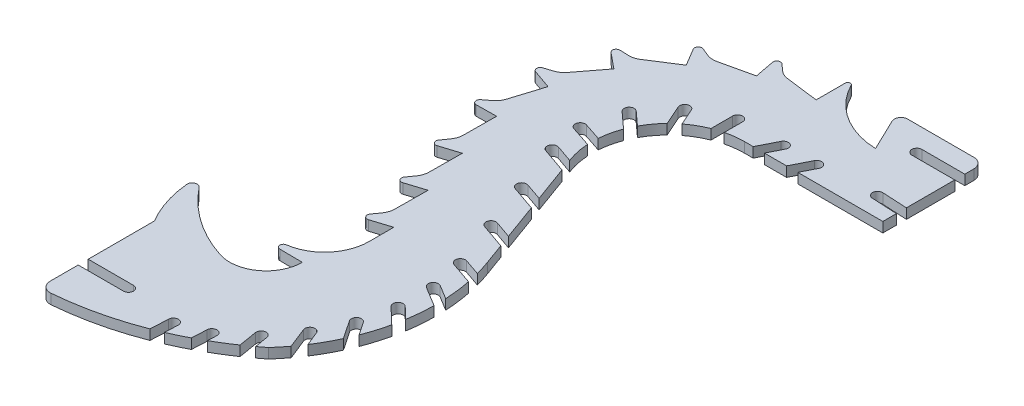
SolidWorks part; units mm, degrees
ref_plane "Front Plane" through (0, 0, 0) normal (0, 0, 1) x (1, 0, 0)
ref_plane "Top Plane" through (0, 0, 0) normal (0, 1, 0) x (1, 0, 0)
ref_plane "Right Plane" through (0, 0, 0) normal (1, 0, 0) x (0, 0, -1)
sketch "Sketch2" plane through (0, 0, 0) normal (0, 1, 0) x (1, 0, 0)
  line L0 (30.5917, -19.7066) -> (10.772, -19.7066)
  line L1 (33.5917, -22.7066) -> (33.5917, -25.4325)
  line L2 (33.5917, -25.4325) -> (20.7417, -25.4325)
  line L3 (20.7417, -28.4325) -> (33.5917, -28.4325)
  line L4 (33.5917, -28.4325) -> (33.5917, -42.9025)
  line L5 (33.5917, -42.9025) -> (26.1381, -42.5119)
  line L6 (25.9811, -45.5078) -> (33.5917, -45.9066)
  line L7 (33.5917, -45.9066) -> (33.5917, -49.9666)
  line L8 (33.5917, -49.9666) -> (8.1353, -49.9666)
  line L9 (-13.2283, -50.6294) -> (-13.2283, -45.1294)
  line L10 (-38.0968, -90.3449) -> (-15.0449, -119.6181) construction
  line L11 (-16.2283, -45.1294) -> (-16.2283, -51.5914)
  line L12 (-21.75, -54.7438) -> (-23.977, -49.7148)
  line L13 (-26.7201, -50.9295) -> (-24.1036, -56.8382)
  line L14 (-27.876, -61.9563) -> (-31.9485, -58.2597)
  line L15 (-33.9648, -60.4811) -> (-29.18, -64.8243)
  line L16 (-30.557, -71.0316) -> (-35.7774, -69.3005)
  line L17 (-36.7216, -72.1481) -> (-30.588, -74.1819)
  line L18 (-1.8534, -49.9666) -> (0.2604, -45.786)
  line L19 (-2.4169, -44.4324) -> (-5.215, -49.9666)
  line L20 (8.1353, -49.9666) -> (10.249, -45.786)
  line L21 (7.5717, -44.4324) -> (4.7736, -49.9666)
  line L22 (4.7736, -49.9666) -> (-1.8534, -49.9666)
  line L23 (-5.215, -49.9666) -> (-7.7629, -49.9666)
  line L24 (8.9709, -22.5761) -> (13.5917, -32.1477)
  line L25 (-7.9083, -19.7066) -> (-7.9083, -28.4325)
  line L26 (-7.9083, -28.4325) -> (-17.7173, -27.1882)
  line L27 (-24.1854, -25.2247) -> (-23.052, -31.1477)
  line L28 (-22.3688, -24.2007) -> (-20.4345, -25.943)
  line L29 (-38.0886, -32.105) -> (-35.6757, -33.0826)
  line L30 (-39.4466, -33.6875) -> (-36.3599, -38.8682)
  line L31 (-23.052, -31.1477) -> (-32.6967, -33.3258)
  line L32 (-50.167, -44.8996) -> (-47.5654, -44.9951)
  line L33 (-50.9034, -46.8506) -> (-46.234, -50.6668)
  line L34 (-36.3599, -38.8682) -> (-44.6822, -44.2069)
  line L35 (-57.1537, -61.0481) -> (-54.6757, -60.25)
  line L36 (-57.1801, -63.1333) -> (-51.4886, -65.1268)
  line L37 (-46.234, -50.6668) -> (-52.2346, -58.5252)
  line L38 (-58.2099, -78.6115) -> (-56.153, -77.0157)
  line L39 (-57.523, -80.5806) -> (-51.4929, -80.512)
  line L40 (-51.4886, -65.1268) -> (-54.4471, -74.5613)
  line L41 (-35.2032, -82.0735) -> (-27.7919, -84.6414)
  line L42 (-34.2211, -79.2389) -> (-29.1162, -81.0076)
  line L43 (-29.3337, -80.4151) -> (-34.808, -80.9462) [skipped]
  line L44 (-34.5184, -83.9321) -> (-28.0865, -83.3082) [skipped]
  line L45 (-27.7919, -84.6414) -> (-23.8627, -95.4227)
  line L46 (-29.9498, -96.4886) -> (-22.5384, -99.0565)
  line L47 (-28.9676, -93.654) -> (-23.8627, -95.4227)
  line L48 (-24.6963, -110.9037) -> (-17.2849, -113.4716)
  line L49 (-23.7142, -108.0691) -> (-18.6093, -109.8378)
  line L50 (-19.4428, -125.3189) -> (-12.8043, -127.6189)
  line L51 (-18.4607, -122.4842) -> (-13.6103, -124.1647)
  line L52 (-17.6104, -135.4043) -> (-11.761, -138.9742)
  line L53 (-16.0476, -132.8435) -> (-11.8298, -135.4176)
  line L55 (-17.9659, -145.6487) -> (-13.1058, -150.2901)
  line L56 (-15.894, -143.4791) -> (-12.4305, -146.7867)
  line L57 (-13.2072, -136.8993) -> (-8.1023, -138.668) [skipped]
  line L58 (-14.1894, -139.734) -> (-6.778, -142.3018) [skipped]
  line L59 (-20.4932, -155.5829) -> (-16.78, -161.0812)
  line L60 (-18.0071, -153.9039) -> (-15.3857, -157.7855)
  line L61 (-25.0765, -164.7517) -> (-22.6311, -170.882)
  line L62 (-22.29, -163.6402) -> (-20.5743, -167.9412)
  line L63 (-31.5058, -172.7353) -> (-30.5908, -178.2262)
  line L64 (-28.5466, -172.2422) -> (-27.8723, -176.2883)
  line L65 (-39.4867, -179.1681) -> (-39.7092, -183.6785)
  line L66 (-36.4904, -179.3159) -> (-36.6228, -182.0006)
  line L67 (-47.9916, -182.1905) -> (-48.2552, -187.533)
  line L68 (-44.9953, -182.3383) -> (-45.1896, -186.2772)
  line L69 (-45.7574, -184.5372) -> (-47.0955, -189.4931) [skipped]
  line L70 (-48.6536, -183.7552) -> (-50.485, -190.538) [skipped]
  line L71 (-52.7805, -97.0521) -> (-47.0301, -95.2357)
  line L72 (-54.0094, -95.3673) -> (-52.5045, -93.243)
  line L73 (-51.4929, -80.512) -> (-51.5847, -90.3991)
  line L74 (-48.3176, -111.7758) -> (-42.5672, -109.9593)
  line L75 (-49.5466, -110.091) -> (-48.0417, -107.9667)
  line L76 (-47.0301, -95.2357) -> (-47.1218, -105.1228)
  line L77 (-43.8548, -126.4995) -> (-38.1043, -124.683)
  line L78 (-45.0837, -124.8147) -> (-43.5788, -122.6904)
  line L79 (-42.5672, -109.9593) -> (-42.659, -119.8465)
  line L80 (-38.1043, -124.683) -> (-38.1043, -132.0985)
  line L81 (-49.4878, -147.407) -> (-42.6952, -147.47)
  line L82 (-75.5719, -158.8868) -> (-75.5719, -178.7068)
  line L83 (-22.5384, -99.0565) -> (-18.6093, -109.8378)
  line L84 (-17.2849, -113.4716) -> (-15.0449, -119.6181)
  line L85 (-75.5719, -181.7068) -> (-62.0122, -181.7068)
  line L86 (-62.0122, -178.7068) -> (-75.5719, -178.7068)
  line L87 (-75.5719, -181.7068) -> (-75.5719, -190.1036)
  arc A0 (-13.2283, -45.1294) -> (-16.2283, -45.1294) centre (-14.7283, -45.1294) ccw
  arc A1 (20.7417, -25.4325) -> (20.7417, -28.4325) centre (20.7417, -26.9325) ccw
  arc A2 (26.1381, -42.5119) -> (25.9811, -45.5078) centre (26.0596, -44.0098) ccw
  arc A3 (-7.7629, -49.9666) -> (-13.2283, -50.6294) centre (-7.7629, -72.8316) ccw
  arc A4 (-15.0449, -119.6181) -> (-13.6103, -124.1647) centre (-66.1611, -138.247) cw
  arc A5 (-25.7152, -174.6342) -> (-27.8723, -176.2883) centre (-79.6425, -106.5423) cw
  arc A6 (-23.977, -49.7148) -> (-26.7201, -50.9295) centre (-25.3485, -50.3222) ccw
  arc A7 (-31.9485, -58.2597) -> (-33.9648, -60.4811) centre (-32.9567, -59.3704) ccw
  arc A8 (-35.7774, -69.3005) -> (-36.7216, -72.1481) centre (-36.2495, -70.7243) ccw
  arc A9 (0.2604, -45.786) -> (-2.4169, -44.4324) centre (-1.0783, -45.1092) ccw
  arc A10 (10.249, -45.786) -> (7.5717, -44.4324) centre (8.9104, -45.1092) ccw
  arc A11 (-20.4345, -25.943) -> (-17.7173, -27.1882) centre (-17.0881, -22.228) ccw
  arc A12 (-16.2283, -51.5914) -> (-21.75, -54.7438) centre (-7.7629, -72.8316) ccw
  arc A13 (-24.1036, -56.8382) -> (-27.876, -61.9563) centre (-7.7629, -72.8316) ccw
  arc A14 (-29.18, -64.8243) -> (-30.557, -71.0316) centre (-7.7629, -72.8316) ccw
  arc A15 (-30.588, -74.1819) -> (-29.1162, -81.0076) centre (-7.7629, -72.8316) ccw
  arc A16 (13.5917, -32.1477) -> (-6.4819, -19.3653) centre (14.3622, -8.7848) cw
  arc A17 (-6.4819, -19.3653) -> (-7.9083, -19.7066) centre (-7.1543, -19.7066) ccw
  arc A18 (-22.3688, -24.2007) -> (-24.1854, -25.2247) centre (-23.105, -25.018) ccw
  arc A19 (-35.6757, -33.0826) -> (-32.6967, -33.3258) centre (-33.7981, -28.4486) ccw
  arc A20 (-38.0886, -32.105) -> (-39.4466, -33.6875) centre (-38.5016, -33.1245) ccw
  arc A21 (-47.5654, -44.9951) -> (-44.6822, -44.2069) centre (-47.382, -39.9984) ccw
  arc A22 (-50.167, -44.8996) -> (-50.9034, -46.8506) centre (-50.2073, -45.9988) ccw
  arc A23 (-54.6757, -60.25) -> (-52.2346, -58.5252) centre (-56.2086, -55.4908) ccw
  arc A24 (-57.1537, -61.0481) -> (-57.1801, -63.1333) centre (-56.8165, -62.0952) ccw
  arc A25 (-56.153, -77.0157) -> (-54.4471, -74.5613) centre (-59.2181, -73.0653) ccw
  arc A26 (-58.2099, -78.6115) -> (-57.523, -80.5806) centre (-57.5356, -79.4806) ccw
  arc A27 (-34.808, -80.9462) -> (-34.5184, -83.9321) centre (-34.6632, -82.4391) ccw [skipped]
  arc A28 (-35.2032, -82.0735) -> (-34.2211, -79.2389) centre (-34.7122, -80.6562) cw
  arc A29 (-29.9498, -96.4886) -> (-28.9676, -93.654) centre (-29.4587, -95.0713) cw
  arc A30 (-24.6963, -110.9037) -> (-23.7142, -108.0691) centre (-24.2052, -109.4864) cw
  arc A31 (-19.4428, -125.3189) -> (-18.4607, -122.4842) centre (-18.9518, -123.9015) cw
  arc A32 (-12.8043, -127.6189) -> (-11.8298, -135.4176) centre (-66.1611, -138.247) cw
  circle A33 centre (-7.7629, -72.8316) radius 44.3994 construction
  arc A34 (-17.6104, -135.4043) -> (-16.0476, -132.8435) centre (-16.829, -134.1239) cw
  arc A35 (-14.1894, -139.734) -> (-13.2072, -136.8993) centre (-13.6983, -138.3166) cw [skipped]
  arc A36 (-17.9659, -145.6487) -> (-15.894, -143.4791) centre (-16.93, -144.5639) cw
  arc A37 (-20.4932, -155.5829) -> (-18.0071, -153.9039) centre (-19.2502, -154.7434) cw
  arc A38 (-25.0765, -164.7517) -> (-22.29, -163.6402) centre (-23.6833, -164.196) cw
  arc A39 (-31.5058, -172.7353) -> (-28.5466, -172.2422) centre (-30.0262, -172.4888) cw
  arc A40 (-39.4867, -179.1681) -> (-36.4904, -179.3159) centre (-37.9885, -179.242) cw
  arc A41 (-47.9916, -182.1905) -> (-44.9953, -182.3383) centre (-46.4934, -182.2644) cw
  arc A42 (-48.6536, -183.7552) -> (-45.7574, -184.5372) centre (-47.2055, -184.1462) cw [skipped]
  arc A43 (-52.5045, -93.243) -> (-51.5847, -90.3991) centre (-56.5845, -90.3527) ccw
  arc A44 (-54.0094, -95.3673) -> (-52.7805, -97.0521) centre (-53.1118, -96.0032) ccw
  arc A45 (-49.5466, -110.091) -> (-48.3176, -111.7758) centre (-48.649, -110.7269) ccw
  arc A46 (-48.0417, -107.9667) -> (-47.1218, -105.1228) centre (-52.1216, -105.0764) ccw
  arc A47 (-45.0837, -124.8147) -> (-43.8548, -126.4995) centre (-44.1861, -125.4506) ccw
  arc A48 (-43.5788, -122.6904) -> (-42.659, -119.8465) centre (-47.6588, -119.8001) ccw
  arc A49 (-38.1043, -132.0985) -> (-49.6306, -145.3108) centre (-51.44, -132.0985) cw
  arc A50 (-49.6306, -145.3108) -> (-49.4878, -147.407) centre (-49.4878, -146.354) ccw
  arc A51 (-42.6952, -147.47) -> (-57.0275, -157.7653) centre (-53.632, -147.3685) cw
  arc A52 (-57.0275, -157.7653) -> (-77.6013, -143.4683) centre (-43.5012, -116.3488) cw
  arc A53 (-77.6013, -143.4683) -> (-80.2278, -144.5253) centre (-78.7573, -144.3877) ccw
  arc A54 (-80.2278, -144.5253) -> (-75.5719, -158.8868) centre (-45.8128, -141.3035) ccw
  arc A55 (-22.6311, -170.882) -> (-25.7152, -174.6342) centre (-66.1611, -138.247) cw
  arc A56 (-30.5908, -178.2262) -> (-36.6228, -182.0006) centre (-79.6425, -106.5423) cw
  arc A57 (-39.7092, -183.6785) -> (-45.1896, -186.2772) centre (-79.6425, -106.5423) cw
  arc A58 (-48.2552, -187.533) -> (-82.1004, -193.3675) centre (-79.6425, -106.5423) cw construction
  arc A59 (-16.78, -161.0812) -> (-20.5743, -167.9412) centre (-66.1611, -138.247) cw
  arc A60 (-13.1058, -150.2901) -> (-15.3857, -157.7855) centre (-66.1611, -138.247) cw
  arc A61 (-11.761, -138.9742) -> (-12.4305, -146.7867) centre (-66.1611, -138.247) cw
  arc A62 (-62.0122, -181.7068) -> (-62.0122, -178.7068) centre (-62.0122, -180.2068) ccw
  arc A63 (10.772, -19.7066) -> (8.9709, -22.5761) centre (10.772, -21.7066) ccw
  arc A64 (30.5917, -19.7066) -> (33.5917, -22.7066) centre (30.5917, -22.7066) cw
  arc A65 (-48.2552, -187.533) -> (-72.3189, -193.093) centre (-79.6425, -106.5423) cw
  arc A66 (-72.3189, -193.093) -> (-75.5719, -190.1036) centre (-72.5719, -190.1036) cw
  point P30 (22.2417, -26.9325)
  point P31 (24.5617, -43.9313)
  point P36 (-14.7283, -43.6294)
  point P208 (-79.3087, -143.0175)
  point P222 (33.5917, -19.7066)
  point P223 (-75.5719, -193.3068)
  dimension "D1" = 22.865
  dimension "D4" = 54.405
  dimension "D6" = 40
  dimension "D7" = 86.86
  dimension "D12" = 1.5
  dimension "D10" = 56.11
  dimension "D22" = 41.5
  dimension "D23" = 187.229
  dimension "D25" = 1.1
  dimension "D27" = 5
  dimension "D33" = 6.1298
  dimension "D40" = 1.5
  dimension "D41" = 1.5
  dimension "D39" = 6.778
  dimension "D42" = 7.1543
  dimension "D43" = 8.1023
  dimension "D44" = 11.761
  dimension "D45" = 12.8043
  dimension "D46" = 13.2072
  dimension "D47" = 13.6103
  dimension "D48" = 15.3857
  dimension "D49" = 15.894
  dimension "D50" = 21.75
  dimension "D51" = 27.8723
  dimension "D74" = 2
  dimension "D75" = 3
  dimension "D76" = 3
  dimension "D2" = 120
  dimension "D3" = 37.26
  dimension "D5" = 62
  dimension "D8" = 46.82
  dimension "D9" = 4.06
  dimension "D11" = 9.03
  dimension "D13" = 3
  dimension "D14" = 11.35
  dimension "D15" = 30.26
  dimension "D16" = 14.47
  dimension "D17" = 7
  dimension "D21" = 20
  dimension "D24" = 10.833
  dimension "D26" = 1
  dimension "D31" = 50.35
  dimension "D32" = 4.8575
  dimension "D34" = 11.0799
  dimension "D35" = 2
  dimension "D37" = 34.42
  dimension "D38" = 11.6
  dimension "D52" = 42.6952
  dimension "D53" = 43.5012
  dimension "D54" = 44.9953
  dimension "D55" = 45.1896
  dimension "D56" = 45.8128
  dimension "D57" = 46.4934
  dimension "D58" = 49.4878
  dimension "D59" = 49.6306
  dimension "D60" = 51.44
  dimension "D61" = 53.632
  dimension "D62" = 57.0275
  dimension "D63" = 13.5596
  dimension "D65" = 79.3087
  dimension "D66" = 8.7848
  dimension "D67" = 33.0668
  dimension "D68" = 72.8316
  dimension "D69" = 5.6615
  dimension "D70" = 27.1379
  dimension "D71" = 9.9886
  dimension "D72" = 5.9141
  dimension "D73" = 64.231
  dimension "D20" = 2
  dimension "D29" = 5
  dimension "D36" = 3
  dimension "D19" = 2
  dimension "D28" = 5
  dimension "D18" = 5
  dimension "D30" = 8
extrude "Boss-Extrude1" add sketch "Sketch2" along normal mid plane 3 contours A62 L85 L87 A58 L67 A41 L68 A57 L65 A40 L66 A56 L63 A39 L64 A5 A55 L61 A38 L62 A59 L59 A37 L60 A60 L55 A36 L56 A61 L52 A34 L53 A32 L50 A31 L51 A4 L84 L48 A30 L49 L83 L46 A29 L47 L45 L41 A28 L42 A15 L17
